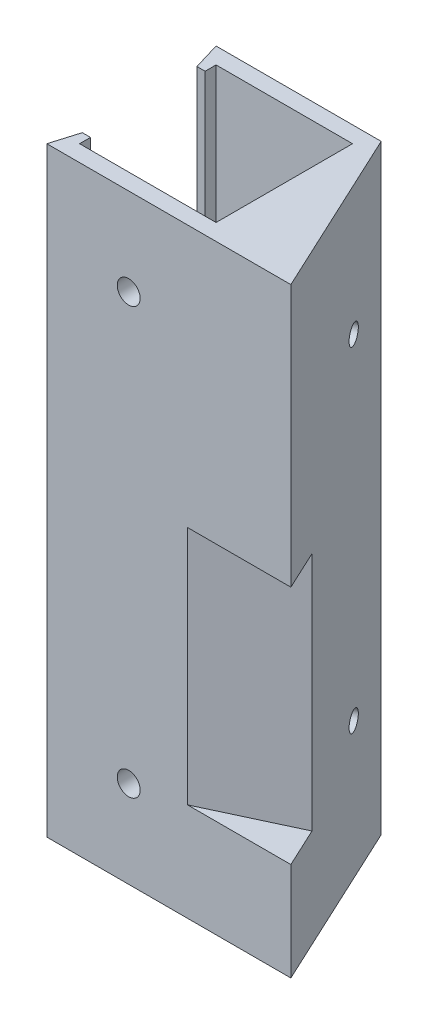
SolidWorks part; units mm, degrees
ref_plane "Спереди" through (0, 0, 0) normal (0, 0, 1) x (1, 0, 0)
ref_plane "Сверху" through (0, 0, 0) normal (0, 1, 0) x (1, 0, 0)
ref_plane "Справа" through (0, 0, 0) normal (1, 0, 0) x (0, 0, -1)
sketch "Эскиз1" plane through (0, 0, 0) normal (0, 1, 0) x (1, 0, 0)
  line L0 (-66.8258, 34.9697) -> (-66.8258, 29.9697)
  line L1 (-63.8258, 29.9697) -> (-63.8258, 31.9697)
  line L2 (-63.8258, 31.9697) -> (-38.8258, 31.9697)
  line L3 (-38.8258, 31.9697) -> (-38.8258, 6.9697)
  line L4 (-38.8258, 6.9697) -> (-63.8258, 6.9697)
  line L5 (-63.8258, 6.9697) -> (-63.8258, 8.9697)
  line L6 (-63.8258, 8.9697) -> (-66.8258, 8.9697)
  line L7 (-66.8258, 8.9697) -> (-66.8258, 3.9697)
  line L8 (-66.8258, 3.9697) -> (-22.1235, 3.9697)
  line L9 (-22.1235, 3.9697) -> (-36.579, 34.9697)
  line L10 (-36.579, 34.9697) -> (-66.8258, 34.9697)
  line L11 (-66.8258, 29.9697) -> (-63.8258, 29.9697)
  point P13 (0, 0)
  point P14 (-63.7308, 29.7758)
  dimension "D1" = 25
  dimension "D2" = 25
  dimension "D3" = 25
  dimension "D4" = 155
  dimension "D5" = 3
  dimension "D6" = 3
  dimension "D7" = 3
  dimension "D8" = 3
  dimension "D9" = 2
  dimension "D10" = 2
extrude "Бобышка-Вытянуть1" add sketch "Эскиз1" along normal blind 110
sketch "Эскиз2" plane through (-16.6516, 0, 7.7648) normal (0.9063, 0, -0.4226) x (-0.4226, 0, -0.9063)
  line L0 (12.9476, 110) -> (12.9476, 0) construction
  line L1 (12.9476, 62) -> (20.9476, 62)
  line L2 (12.9476, 62) -> (12.9476, 18)
  line L3 (12.9476, 18) -> (20.9476, 18)
  line L4 (20.9476, 62) -> (20.9476, 18)
  line L5 (12.9476, 0) -> (47.1523, 0) construction
  dimension "D1" = 8
  dimension "D2" = 44
  dimension "D3" = 18
extrude "Вырез-Вытянуть3" cut sketch "Эскиз2" against normal blind 110
sketch "Эскиз3" plane through (0, 0, 0) normal (0, -1, 0) x (1, 0, 0)
  line L0 (-66.8258, -3.9697) -> (-65.3258, -8.9697)
  line L1 (-63.8258, -8.9697) -> (-66.8258, -8.9697) construction
  line L2 (-65.3258, -8.9697) -> (-66.8258, -8.9697)
  line L3 (-66.8258, -8.9697) -> (-66.8258, -3.9697)
  line L4 (-66.8258, -29.9697) -> (-66.8258, -34.9697)
  line L5 (-66.8258, -34.9697) -> (-65.3258, -29.9697)
  line L6 (-66.8258, -29.9697) -> (-63.8258, -29.9697) construction
  line L7 (-65.3258, -29.9697) -> (-66.8258, -29.9697)
extrude "Вырез-Вытянуть4" cut sketch "Эскиз3" against normal through all
sketch "Эскиз4" plane through (-16.6516, 0, 7.7648) normal (0.9063, 0, -0.4226) x (-0.4226, 0, -0.9063)
  line L0 (36.7476, 110) -> (36.7476, 0) construction
  line L1 (12.9476, 110) -> (47.1523, 110) construction
  line L2 (12.9476, 0) -> (47.1523, 0) construction
  line L3 (20.9476, 18) -> (20.9476, 62) construction
  line L4 (20.9476, 25) -> (47.1523, 25) construction
  line L5 (47.1523, 110) -> (47.1523, 0) construction
  line L6 (12.9476, 86.3) -> (47.1523, 86.3) construction
  line L7 (12.9476, 110) -> (12.9476, 62) construction
  circle A0 centre (36.7476, 86.3) radius 1.75
  circle A1 centre (36.7476, 25) radius 1.75
  dimension "D1" = 15.8
  dimension "D2" = 25
  dimension "D3" = 61.3
extrude "Вырез-Вытянуть6" cut sketch "Эскиз4" against normal blind 10
sketch "Эскиз5" plane through (-16.6516, 0, 7.7648) normal (0.9063, 0, -0.4226) x (-0.4226, 0, -0.9063)
  line L1 (40.789, 86.3) -> (38.7683, 89.8)
  line L2 (38.7683, 89.8) -> (34.7269, 89.8)
  line L3 (34.7269, 89.8) -> (32.7061, 86.3)
  line L4 (32.7061, 86.3) -> (34.7269, 82.8)
  line L5 (34.7269, 82.8) -> (38.7683, 82.8)
  line L6 (38.7683, 82.8) -> (40.789, 86.3)
  line L7 (40.789, 25) -> (38.7683, 28.5)
  line L8 (38.7683, 28.5) -> (34.7269, 28.5)
  line L9 (34.7269, 28.5) -> (32.7061, 25)
  line L10 (32.7061, 25) -> (34.7269, 21.5)
  line L11 (34.7269, 21.5) -> (38.7683, 21.5)
  line L12 (38.7683, 21.5) -> (40.789, 25)
  circle A0 centre (36.7476, 86.3) radius 3.5 construction
  circle A1 centre (36.7476, 25) radius 3.5 construction
extrude "Вырез-Вытянуть11" cut sketch "Эскиз5" against normal blind 10 from offset 2.5 offset against normal yes
sketch "Эскиз6" plane through (0, 0, -3.9697) normal (0, 0, 1) x (1, 0, 0)
  line L0 (-51.8258, 110) -> (-51.8258, 0) construction
  line L1 (-66.8258, 110) -> (-22.1235, 110) construction
  line L2 (-66.8258, 0) -> (-22.1235, 0) construction
  line L3 (-66.8258, 94) -> (-22.1235, 94) construction
  line L4 (-66.8258, 110) -> (-66.8258, 0) construction
  line L5 (-22.1235, 110) -> (-22.1235, 62) construction
  line L6 (-65.1688, 16) -> (-66.8258, 16) construction
  line L7 (-66.8258, 16) -> (-22.1235, 16) construction
  line L8 (-22.1235, 18) -> (-22.1235, 0) construction
  circle A0 centre (-51.8258, 94) radius 2.1
  circle A1 centre (-51.8258, 16) radius 2.1
  dimension "D1" = 15
  dimension "D2" = 16
  dimension "D3" = 16
extrude "Вырез-Вытянуть13" cut sketch "Эскиз6" against normal through all
